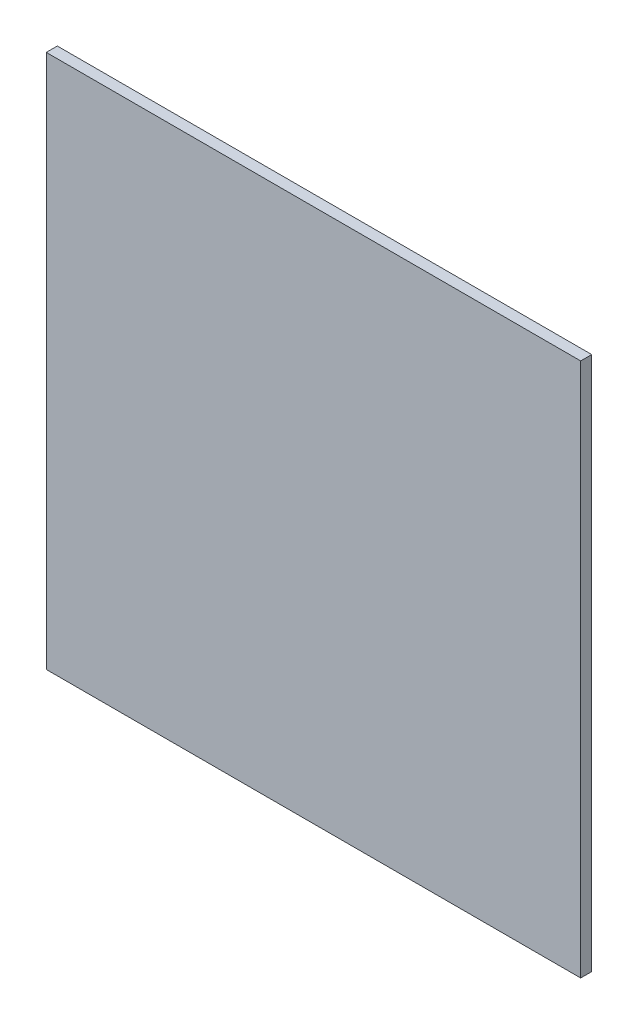
SolidWorks part; units mm, degrees
ref_plane "Спереди" through (0, 0, 0) normal (0, 0, 1) x (1, 0, 0)
ref_plane "Сверху" through (0, 0, 0) normal (0, 1, 0) x (1, 0, 0)
ref_plane "Справа" through (0, 0, 0) normal (1, 0, 0) x (0, 0, -1)
other "Configuration Table"
sketch "Эскиз1" plane through (0, 0, 0) normal (0, 0, 1) x (1, 0, 0)
  line L1 (-72.5, -72.5) -> (72.5, -72.5)
  line L2 (-72.5, -72.5) -> (-72.5, 72.5)
  line L3 (-72.5, 72.5) -> (72.5, 72.5)
  line L4 (72.5, -72.5) -> (72.5, 72.5)
  line L5 (-72.5, -72.5) -> (72.5, 72.5) construction
  line L6 (-72.5, 72.5) -> (72.5, -72.5) construction
  point P0 (0, 0)
  dimension "D1" = 145
  dimension "D2" = 145
extrude "Панель" add sketch "Эскиз1" along normal blind 3
